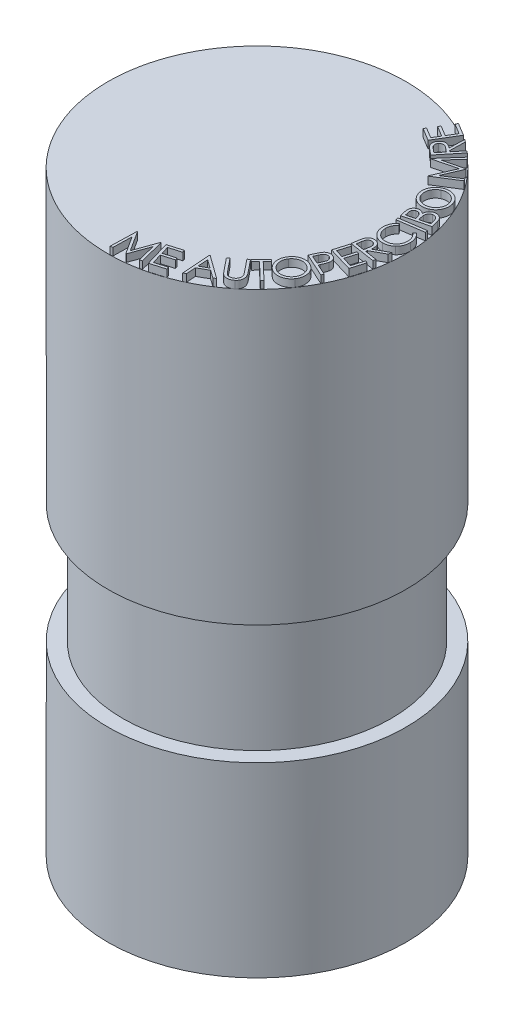
SolidWorks part; units mm, degrees
ref_plane "Alzado" through (0, 0, 0) normal (0, 0, 1) x (1, 0, 0)
ref_plane "Planta" through (0, 0, 0) normal (0, 1, 0) x (1, 0, 0)
ref_plane "Vista lateral" through (0, 0, 0) normal (1, 0, 0) x (0, 0, -1)
sketch "Croquis1" plane through (0, 0, 0) normal (0, 1, 0) x (1, 0, 0)
  circle A0 centre (0, 0) radius 20
  dimension "D1" = 40
extrude "Saliente-Extruir1" add sketch "Croquis1" along normal blind 80
sketch "Croquis2" plane through (0, 0, 0) normal (1, 0, 0) x (0, 0, -1)
  line L0 (0, -3.3102) -> (0, 88.3441) construction
  line L1 (20, 0) -> (20, 80) construction
  line L2 (20, 41) -> (18, 41)
  line L3 (20, 41) -> (20, 25)
  line L4 (20, 25) -> (18, 25)
  line L5 (18, 41) -> (18, 25)
  line L6 (-20, 0) -> (20, 0) construction
  dimension "D1" = 16
  dimension "D2" = 2
  dimension "D3" = 25
revolve "Cortar-Revolución1" cut sketch "Croquis2" angle 360 about L0
sketch "Croquis3" plane through (0, 80, 0) normal (0, 1, 0) x (1, 0, 0)
  text T0 "ME AUTOPERCIBO MRE" font "Century Gothic" height 3.5
extrude "Saliente-Extruir2" add sketch "Croquis3" along normal blind 1
